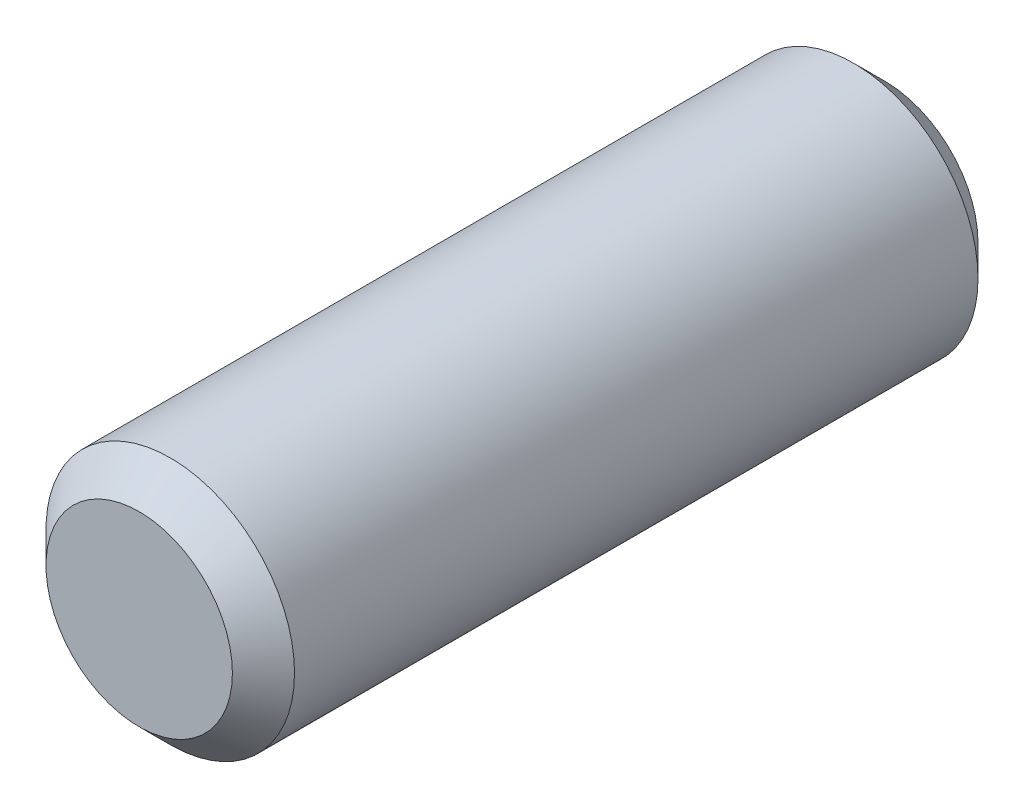
SolidWorks part; units mm, degrees
ref_plane "Front Plane" through (0, 0, 0) normal (1, 0, 0) x (0, 1, 0)
ref_plane "Top Plane" through (0, 0, 0) normal (0, 0, 1) x (0, 1, 0)
ref_plane "Right Plane" through (0, 0, 0) normal (0, 1, 0) x (-1, 0, 0)
sketch "Sketch1" plane through (0, 0, 0) normal (0, 0, 1) x (0, 1, 0)
  circle A0 centre (0, 0) radius 4
  dimension "D1" = 8
extrude "Boss-Extrude1" add sketch "Sketch1" along normal mid plane 24
chamfer "Chamfer1" distance 1 angle 45 2 edges at (4, 0, -12) (4, 0, 12)
